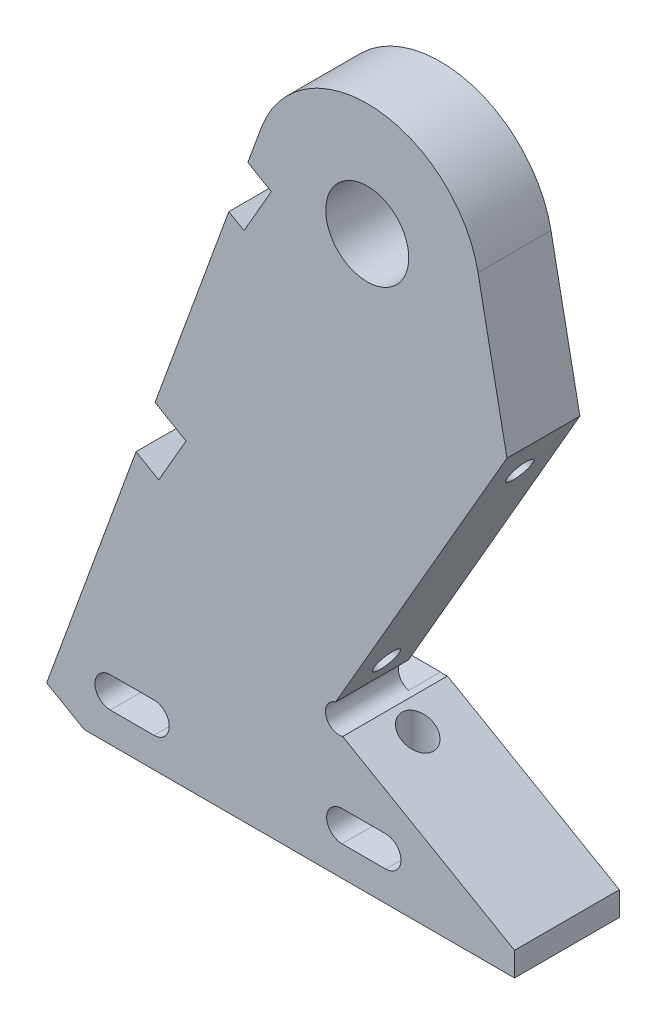
SolidWorks part; units mm, degrees
ref_plane "Front Plane" through (0, 0, 0) normal (0, 0, 1) x (1, 0, 0)
ref_plane "Top Plane" through (0, 0, 0) normal (0, 1, 0) x (1, 0, 0)
ref_plane "Right Plane" through (0, 0, 0) normal (1, 0, 0) x (0, 0, -1)
sketch "Model" plane through (0, 0, 0) normal (0, 0, 1) x (1, 0, 0)
  line L0 (30.032, -29.5212) -> (30.032, -26.7298)
  line L1 (-3.1895, 31.0479) -> (-11.7681, 7.5374)
  line L2 (12.4426, -6.5562) -> (9.2271, -12.1257) construction
  line L3 (16.6788, -19.0204) -> (10.0488, -15.1925) construction
  line L4 (9.6915, -11.3213) -> (10.8533, -15.657) construction
  line L5 (10.2724, -13.4891) -> (9.0035, -13.8291) construction
  line L6 (29.1519, 22.385) -> (9.2271, -12.1257)
  line L7 (30.032, -26.7298) -> (10.0488, -15.1925)
  line L8 (9.3745, -14.8032) -> (2.5284, -10.8506) construction
  line L9 (9.0235, -12.4784) -> (5.2305, -19.0481) construction
  line L10 (0.5709, 41.3535) -> (-0.9796, 37.1044)
  line L11 (0.0253, 32.858) -> (-15.4747, 6.0112) construction
  line L12 (-11.7681, 7.5374) -> (-8.1659, 5.4577)
  line L13 (-15.4747, 6.0112) -> (10.9052, -9.2192) construction
  line L14 (-11.7681, 7.5374) -> (-13.8872, 8.7609) construction
  line L15 (-11.3408, -0.0416) -> (-13.978, 1.4809) construction
  line L16 (-8.1659, 5.4577) -> (-11.3408, -0.0416)
  line L17 (-11.3408, -0.0416) -> (-13.978, 1.4809)
  line L18 (-13.978, 1.4809) -> (-24.3737, -27.0097)
  line L19 (0.0253, 32.858) -> (26.4052, 17.6276) construction
  line L20 (-1.4214, 30.0271) -> (1.7536, 35.5264)
  line L21 (-0.9796, 37.1044) -> (1.7536, 35.5264)
  line L22 (-3.1895, 31.0479) -> (-1.4214, 30.0271)
  line L23 (11.3113, 26.3421) -> (-4.1887, -0.5047) construction
  line L24 (3.5613, 12.9187) -> (-2.5691, 16.458) construction
  line L25 (12.2357, 35.6885) -> (0.2074, 14.855) construction
  line L26 (0.2074, 14.855) -> (12.9074, 36.8521) construction
  line L28 (29.1519, 22.385) -> (25.7905, 39.3975)
  line L80 (-20.0226, -29.5212) -> (-24.3737, -27.0097)
  line L82 (30.032, -29.5212) -> (-20.0226, -29.5212)
  circle A0 centre (12.9074, 36.8521) radius 3.175
  arc A2 (9.2271, -12.1257) -> (10.0488, -15.1925) centre (9.638, -13.6591) ccw
  arc A3 (25.7905, 39.3975) -> (0.5709, 41.3535) centre (12.9074, 36.8521) ccw
  point P11 (8.1045, -14.07)
  point P12 (8.1045, -14.07)
  point P37 (0.1661, 32.7767)
  dimension "D1" = 3.175
  dimension "D7" = 6.35
  dimension "D2" = 31
  dimension "D3" = 3.175
  dimension "D4" = 3.175
  dimension "D5" = 6.35
  dimension "D6" = 25.4
extrude "Boss-Extrude1" add sketch "Model" along normal blind 8.4836
hole_wizard "#4 Clearance Hole3" positions "Sketch8" profile "Sketch9" hole size "#4" standard "ANSI Inch" end condition through all
sketch "Sketch8" plane through (-14.0682, 8.1223, 0) normal (-0.866, 0.5, 0) x (0, 0, 1)
  line L0 (8.4836, 25.2935) -> (0, 31.6435) construction
  point P7 (4.2418, 28.4685)
sketch "Sketch9" plane through (0.1661, 32.7767, 4.2418) normal (0, 0, 1) x (-0.5, -0.866, 0)
  line L0 (0, 0) -> (0, 57.0136)
  line L1 (0, 57.0136) -> (1.4732, 57.0136)
  line L2 (1.4732, 57.0136) -> (1.4732, 0)
  line L5 (1.4732, 0) -> (0, 0)
  line L11 (0, -6.35) -> (0, 107.95) construction
  dimension "Thru Hole Dia." = 2.9464
  dimension "Thru Hole Depth" = 57.0136
hole_wizard "#4 Clearance Hole4" positions "Sketch10" profile "Sketch11" hole size "#4" standard "ANSI Inch" end condition through all
sketch "Sketch10" plane through (-8.4878, 4.9001, 0) normal (-0.866, 0.5, 0) x (0, 0, 1)
  line L0 (0, 0.6438) -> (8.4836, -5.7062) construction
  point P7 (4.2418, -2.5312)
sketch "Sketch11" plane through (-9.7533, 2.708, 4.2418) normal (0, 0, 1) x (-0.5, -0.866, 0)
  line L0 (0, 0) -> (0, 50.5695)
  line L1 (0, 50.5695) -> (1.4732, 50.5695)
  line L2 (1.4732, 50.5695) -> (1.4732, 0)
  line L5 (1.4732, 0) -> (0, 0)
  line L11 (0, -6.35) -> (0, 107.95) construction
  dimension "Thru Hole Dia." = 2.9464
  dimension "Thru Hole Depth" = 50.5695
sketch "Sketch12" plane through (0, 0, 0) normal (0, 0, -1) x (-1, 0, 0)
  line L0 (-59.7491, -15.1956) -> (-12.6102, -15.1956) construction
  line L1 (20.0226, -29.5212) -> (-30.032, -29.5212) construction
  line L2 (20.063, -15.1956) -> (-9.2387, -15.1956)
  line L3 (13.978, 1.4809) -> (24.3737, -27.0097) construction
  line L4 (-10.0488, -15.1925) -> (-30.032, -26.7298)
  line L5 (-30.032, -26.7298) -> (-30.032, -29.5212)
  line L6 (-30.032, -29.5212) -> (20.0226, -29.5212)
  line L7 (20.0226, -29.5212) -> (24.3737, -27.0097)
  line L8 (24.3737, -27.0097) -> (20.063, -15.1956)
  line L9 (-9.2387, -15.1956) -> (56.9978, -15.1956) construction
  arc A0 (-10.0488, -15.1925) -> (-9.2387, -15.1956) centre (-9.638, -13.6591) ccw
  dimension "D1" = 14.3256
extrude "Boss-Extrude2" add sketch "Sketch12" along normal blind 3.7084
sketch "Sketch14" plane through (0, 0, 8.4836) normal (0, 0, 1) x (1, 0, 0)
  line L0 (-14.4346, -29.5212) -> (-14.4346, -15.1956) construction
  line L1 (-20.0226, -29.5212) -> (30.032, -29.5212) construction
  line L2 (-20.063, -15.1956) -> (9.2387, -15.1956) construction
  line L3 (-20.0226, -29.5212) -> (-20.0226, -19.7811) construction
  line L4 (-29.6838, -24.2634) -> (35.3142, -24.2634) construction
  line L5 (-16.9746, -24.2634) -> (-11.8946, -24.2634) construction
  line L6 (-16.9746, -22.4854) -> (-11.8946, -22.4854)
  line L7 (-16.9746, -26.0414) -> (-11.8946, -26.0414)
  line L8 (9.9662, -24.2634) -> (15.0462, -24.2634) construction
  line L9 (9.9662, -22.4854) -> (15.0462, -22.4854)
  line L10 (9.9662, -26.0414) -> (15.0462, -26.0414)
  arc A0 (-16.9746, -22.4854) -> (-16.9746, -26.0414) centre (-16.9746, -24.2634) ccw
  arc A1 (-11.8946, -26.0414) -> (-11.8946, -22.4854) centre (-11.8946, -24.2634) ccw
  arc A2 (9.9662, -22.4854) -> (9.9662, -26.0414) centre (9.9662, -24.2634) ccw
  arc A3 (15.0462, -26.0414) -> (15.0462, -22.4854) centre (15.0462, -24.2634) ccw
  point P11 (-14.4346, -24.2634)
  point P14 (-14.4346, -24.2634)
  point P21 (12.5062, -24.2634)
  dimension "D4" = 1.778
  dimension "D1" = 5.588
  dimension "D3" = 5.08
  dimension "D5" = 5.2578
extrude "Cut-Extrude1" cut sketch "Sketch14" against normal through all
hole_wizard "#6 Clearance Hole2" positions "Sketch18" profile "Sketch19" hole size "#6" standard "ANSI Inch"
sketch "Sketch18" plane through (0, -29.5212, 0) normal (0, -1, 0) x (-1, 0, 0)
  point P0 (14.4338, -2.2122)
  point P3 (-12.5069, -2.2122)
sketch "Sketch19" plane through (-14.4338, -29.5212, 2.2122) normal (1, 0, 0) x (0, 0, -1)
  line L0 (0, 0) -> (0, 15.4245)
  line L1 (0, 15.4245) -> (1.8288, 14.3256)
  line L2 (1.8288, 14.3256) -> (1.8288, 0)
  line L5 (1.8288, 0) -> (0, 0)
  line L10 (0, 15.4245) -> (-1.8288, 14.3256) construction
  line L11 (0, -6.35) -> (0, 107.95) construction
  dimension "Hole Dia." = 3.6576
  dimension "Hole Depth" = 14.3256
  dimension "Drill Angle" = 118
sketch "Sketch20" plane through (0, 0, 8.4836) normal (0, 0, 1) x (1, 0, 0)
  circle A0 centre (12.9074, 36.8521) radius 4.826
  dimension "D1" = 9.652
extrude "Cut-Extrude2" cut sketch "Sketch20" against normal through all
